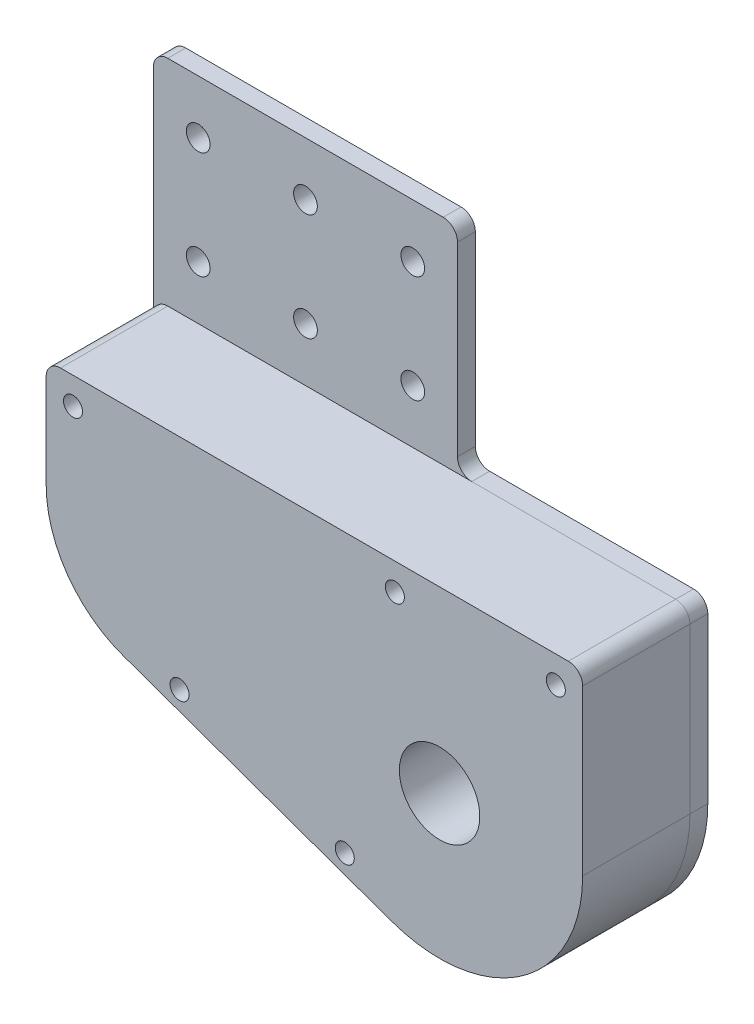
SolidWorks part; units mm, degrees
ref_plane "Front Plane" through (0, 0, 0) normal (0, 0, 1) x (1, 0, 0)
ref_plane "Top Plane" through (0, 0, 0) normal (0, 1, 0) x (1, 0, 0)
ref_plane "Right Plane" through (0, 0, 0) normal (1, 0, 0) x (0, 0, -1)
sketch "Gear&Motor Layout" plane through (0, 0, 0) normal (0, 0, 1) x (1, 0, 0)
  line L1 (-139.7, 63.5) -> (50.8, 63.5) construction
  line L2 (-98.4907, 24.9428) -> (0, 0) construction
  circle A1 centre (-98.4907, 24.9428) radius 32.2072 construction
  circle A2 centre (0, 0) radius 14.2875 construction
  circle A3 centre (-98.4907, 24.9428) radius 25.4 construction
  circle A4 centre (-123.8907, 24.9428) radius 2.5527 construction
  circle A5 centre (-98.4907, 50.3428) radius 2.5527 construction
  circle A6 centre (-73.0907, 24.9428) radius 2.5527 construction
  circle A7 centre (-98.4907, -0.4572) radius 2.5527 construction
  circle A11 centre (-50.4765, 12.7832) radius 41.91 construction
  circle A12 centre (-50.4765, 12.7832) radius 43.18 construction
  circle A15 centre (0, 0) radius 38.1 construction
  circle A16 centre (0, 0) radius 39.37 construction
  circle A17 centre (-50.4765, 12.7832) radius 13.97 construction
  circle A18 centre (-50.4765, 12.7832) radius 15.24 construction
  circle A19 centre (-98.4907, 24.9428) radius 7.62 construction
  circle A20 centre (-98.4907, 24.9428) radius 8.89 construction
  point P5 (-123.8907, 24.9428)
  point P8 (-98.4907, 50.3428)
  point P10 (-73.0907, 24.9428)
  point P14 (-98.4907, -0.4572)
  dimension "D4" = 83.82
  dimension "D1" = 28.575
  dimension "D2" = 64.4144
  dimension "D3" = 50.8
  dimension "D5" = 15.24
  dimension "D6" = 17.78
  dimension "D7" = 86.36
  dimension "D8" = 27.94
  dimension "D9" = 30.48
  dimension "D10" = 76.2
  dimension "D11" = 78.74
  dimension "D13" = 63.5
  dimension "D14" = 5.1054
  dimension "D16" = 6.35
  dimension "D12" = 50.8
  dimension "D15" = 190.5
sketch "Sketch2" plane through (0, 0, 0) normal (0, 0, 1) x (1, 0, 0)
  line L0 (50.8, 63.5) -> (-139.7, 63.5)
  line L1 (50.8, 63.5) -> (50.8, 0)
  line L2 (-17.0643, -47.8482) -> (-112.3334, -13.872)
  line L3 (-139.7, 24.9428) -> (-139.7, 63.5)
  arc A0 (50.8, 0) -> (-17.0643, -47.8482) centre (0, 0) cw
  arc A1 (-112.3334, -13.872) -> (-139.7, 24.9428) centre (-98.4907, 24.9428) cw
extrude "Boss-Extrude1" add sketch "Sketch2" against normal blind 6.35
sketch "Sketch3" plane through (0, 0, 0) normal (0, 0, 1) x (1, 0, 0)
  line L0 (-139.7, 63.5) -> (-139.7, 139.7)
  line L1 (-139.7, 139.7) -> (-31.75, 139.7)
  line L2 (-31.75, 139.7) -> (-31.75, 63.5)
  line L5 (50.8, 0) -> (50.8, 63.5) construction
  line L6 (50.8, 63.5) -> (-139.7, 63.5) construction
  line L7 (-31.75, 63.5) -> (-139.7, 63.5)
  dimension "D1" = 82.55
  dimension "D2" = 76.2
extrude "Boss-Extrude2" add sketch "Sketch3" against normal up to surface (6.35 mm away) up to face at (-50.1578, 11.3816, -6.35)
fillet "Fillet1" radius 5.08 4 edges at (50.8, 63.5, -3.175) (-31.75, 63.5, -3.175) (-31.75, 139.7, -3.175) (-139.7, 139.7, -3.175)
sketch "Sketch4" plane through (0, 0, 0) normal (0, 0, 1) x (1, 0, 0)
  circle A0 centre (0, 0) radius 14.2875 construction
  circle A1 centre (0, 0) radius 14.2875
  circle A2 centre (-50.4765, 12.7832) radius 14.2875 construction
  circle A3 centre (-98.4907, 24.9428) radius 32.2024 construction
  dimension "D1" = 64.4049
extrude "Cut-Extrude1" cut sketch "Sketch4" against normal up to next
hole_wizard "Tap Drill for 1/4-20 Tap1" positions "Sketch10" profile "Sketch9" hole size "1/4-20" standard "ANSI Inch" end condition through all
sketch "Sketch10" plane through (0, 0, 0) normal (0, 0, 1) x (1, 0, 0)
  line L0 (50.8, 0) -> (50.8, 58.42) construction
  line L1 (-139.7, 63.5) -> (50.8, 63.5) construction
  line L2 (-92.345, -14.2588) -> (-33.672, -35.1836) construction
  line L4 (-112.3334, -13.872) -> (-17.0643, -47.8482) construction
  line L5 (-33.672, -35.1836) -> (-30.1524, -25.3146) construction
  line L6 (-89.3815, -5.9494) -> (-92.345, -14.2588) construction
  line L7 (-139.7, 134.62) -> (-139.7, 24.9428) construction
  circle A0 centre (-50.4765, 12.7832) radius 43.18 construction
  circle A1 centre (0, 0) radius 39.37 construction
  circle A2 centre (-98.4907, 24.9428) radius 32.2072 construction
  point P0 (-33.672, -35.1836)
  point P2 (-92.345, -14.2588)
  point P4 (-130.175, 53.975)
  point P6 (-15.875, 53.975)
  point P8 (41.275, 53.975)
  dimension "D1" = 9.525
  dimension "D2" = 9.525
  dimension "D3" = 6.35
  dimension "2" = 57.15
  dimension "D4" = 9.525
  dimension "D5" = 9.525
sketch "Sketch9" plane through (-33.672, -35.1836, 0) normal (1, 0, 0) x (0, -1, 0)
  line L0 (0, 0) -> (0, 6.35)
  line L1 (0, 6.35) -> (2.5527, 6.35)
  line L2 (2.5527, 6.35) -> (2.5527, 0)
  line L5 (2.5527, 0) -> (0, 0)
  line L11 (0, -6.35) -> (0, 107.95) construction
  dimension "Thru Hole Dia." = 5.1054
  dimension "Thru Hole Depth" = 6.35
hole_wizard "5/16 Clearance Hole1" positions "Sketch14" profile "Sketch12" hole size "5/16" standard "ANSI Inch" end condition through all
sketch "Sketch14" plane through (0, 0, 0) normal (0, 0, 1) x (1, 0, 0)
  line L0 (-139.7, 134.62) -> (-139.7, 24.9428) construction
  line L1 (-31.75, 68.58) -> (-31.75, 134.62) construction
  line L2 (-123.825, 82.55) -> (-85.725, 82.55) construction
  line L4 (-47.625, 82.55) -> (-85.725, 82.55) construction
  line L6 (-47.625, 120.65) -> (-47.625, 82.55) construction
  line L8 (-36.83, 139.7) -> (-134.62, 139.7) construction
  point P0 (-123.825, 120.65)
  point P2 (-85.725, 120.65)
  point P4 (-47.625, 120.65)
  point P6 (-47.625, 82.55)
  point P8 (-85.725, 82.55)
  point P10 (-123.825, 82.55)
  point P35 (-47.625, 101.6)
  dimension "D1" = 15.875
  dimension "D2" = 15.875
  dimension "D3" = 38.1
  dimension "D4" = 38.1
sketch "Sketch12" plane through (-123.825, 120.65, 0) normal (1, 0, 0) x (0, -1, 0)
  line L0 (0, 0) -> (0, 6.35)
  line L1 (0, 6.35) -> (4.2164, 6.35)
  line L2 (4.2164, 6.35) -> (4.2164, 0)
  line L5 (4.2164, 0) -> (0, 0)
  line L11 (0, -6.35) -> (0, 107.95) construction
  dimension "Thru Hole Dia." = 8.4328
  dimension "Thru Hole Depth" = 6.35
sketch "Sketch15" plane through (0, 0, 0) normal (0, 0, 1) x (1, 0, 0)
  line L0 (-112.3334, -13.872) -> (-17.0643, -47.8482) construction
  line L1 (50.8, 0) -> (50.8, 58.42) construction
  line L3 (-112.3334, -13.872) -> (-17.0643, -47.8482)
  line L4 (50.8, 0) -> (50.8, 58.42)
  line L6 (-139.7, 24.9428) -> (-139.7, 58.42)
  line L7 (-134.62, 63.5) -> (45.72, 63.5)
  arc A0 (-139.7, 24.9428) -> (-112.3334, -13.872) centre (-98.4907, 24.9428) ccw construction
  arc A1 (-17.0643, -47.8482) -> (50.8, 0) centre (0, 0) ccw construction
  arc A2 (50.8, 58.42) -> (45.72, 63.5) centre (45.72, 58.42) ccw construction
  arc A3 (-139.7, 24.9428) -> (-112.3334, -13.872) centre (-98.4907, 24.9428) ccw
  arc A4 (-17.0643, -47.8482) -> (50.8, 0) centre (0, 0) ccw
  arc A5 (50.8, 58.42) -> (45.72, 63.5) centre (45.72, 58.42) ccw
  arc A6 (-139.7, 58.42) -> (-134.62, 63.5) centre (-134.62, 58.42) cw
  circle A12 centre (0, 0) radius 14.2875
extrude "Boss-Extrude3" add sketch "Sketch15" along normal blind 38.1 separate body
sketch "Sketch16" plane through (0, 0, 38.1) normal (0, 0, 1) x (1, 0, 0)
  circle A0 centre (-15.875, 53.975) radius 3.3782 construction
  circle A1 centre (-15.875, 53.975) radius 3.3782
  circle A2 centre (-92.345, -14.2588) radius 3.3782 construction
  circle A3 centre (-33.672, -35.1836) radius 3.3782 construction
  circle A12 centre (41.275, 53.975) radius 3.3782 construction
  circle A13 centre (-130.175, 53.975) radius 3.3782 construction
  circle A14 centre (-92.345, -14.2588) radius 3.3782
  circle A15 centre (-33.672, -35.1836) radius 3.3782
  circle A16 centre (41.275, 53.975) radius 3.3782
  circle A17 centre (-130.175, 53.975) radius 3.3782
extrude "Cut-Extrude3" cut sketch "Sketch16" against normal up to next (38.1 mm away)
